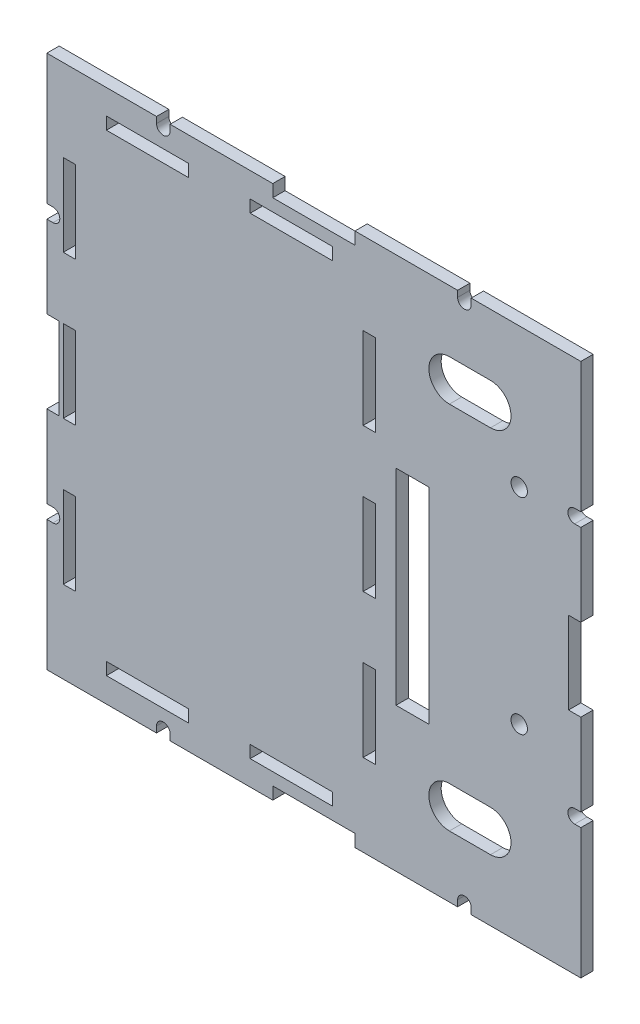
SolidWorks part; units mm, degrees
ref_plane "Front Plane" through (0, 0, 0) normal (0, 0, 1) x (1, 0, 0)
ref_plane "Top Plane" through (0, 0, 0) normal (0, 1, 0) x (1, 0, 0)
ref_plane "Right Plane" through (0, 0, 0) normal (1, 0, 0) x (0, 0, -1)
sketch "Sketch1" plane through (0, 0, 0) normal (0, 0, 1) x (1, 0, 0)
  line L0 (55, 0) -> (-55, 0) construction
  line L1 (65, -65) -> (-65, -65)
  line L2 (65, -65) -> (65, 65)
  line L3 (65, 65) -> (-65, 65)
  line L4 (-65, -65) -> (-65, 65)
  line L5 (65, -65) -> (-65, 65) construction
  line L6 (65, 65) -> (-65, -65) construction
  line L7 (10, 62) -> (-10, 62)
  line L8 (10, 62) -> (10, 65)
  line L9 (10, 65) -> (-10, 65)
  line L10 (-10, 62) -> (-10, 65)
  line L11 (10, 62) -> (-10, 65) construction
  line L12 (10, 65) -> (-10, 62) construction
  line L13 (-62, -10) -> (-65, -10)
  line L14 (-62, -10) -> (-62, 10)
  line L15 (-62, 10) -> (-65, 10)
  line L16 (-65, -10) -> (-65, 10)
  line L17 (-62, -10) -> (-65, 10) construction
  line L18 (-62, 10) -> (-65, -10) construction
  line L19 (10, -65) -> (-10, -65)
  line L20 (-10, -62) -> (-10, -65)
  line L21 (10, -62) -> (-10, -62)
  line L22 (10, -62) -> (10, -65)
  line L23 (0, -55) -> (0, 55) construction
  line L24 (62, 10) -> (65, 10)
  line L25 (65, -10) -> (65, 10)
  line L26 (62, -10) -> (65, -10)
  line L27 (62, -10) -> (62, 10)
  line L28 (-36.65, 63.5) -> (-36.65, 66.5) construction
  line L29 (-38.3, 63.5) -> (-38.3, 66.5)
  line L30 (-35, 63.5) -> (-35, 66.5)
  line L31 (-63.5, 31.65) -> (-66.5, 31.65) construction
  line L32 (-63.5, 30) -> (-66.5, 30)
  line L33 (-63.5, 33.3) -> (-66.5, 33.3)
  line L34 (36.65, 63.5) -> (36.65, 66.5) construction
  line L35 (38.3, 63.5) -> (38.3, 66.5)
  line L36 (35, 63.5) -> (35, 66.5)
  line L37 (63.5, 31.65) -> (66.5, 31.65) construction
  line L38 (63.5, 30) -> (66.5, 30)
  line L39 (63.5, 33.3) -> (66.5, 33.3)
  line L40 (63.5, -31.65) -> (66.5, -31.65) construction
  line L41 (63.5, -30) -> (66.5, -30)
  line L42 (63.5, -33.3) -> (66.5, -33.3)
  line L43 (36.65, -63.5) -> (36.65, -66.5) construction
  line L44 (38.3, -63.5) -> (38.3, -66.5)
  line L45 (35, -63.5) -> (35, -66.5)
  line L46 (-36.65, -63.5) -> (-36.65, -66.5) construction
  line L47 (-38.3, -63.5) -> (-38.3, -66.5)
  line L48 (-35, -63.5) -> (-35, -66.5)
  line L49 (-63.5, -31.65) -> (-66.5, -31.65) construction
  line L50 (-63.5, -30) -> (-66.5, -30)
  line L51 (-63.5, -33.3) -> (-66.5, -33.3)
  line L52 (-58, -45) -> (-61, -45)
  line L53 (-58, -10) -> (-61, -10)
  line L54 (-58, -10) -> (-58, 10)
  line L55 (-58, 10) -> (-61, 10)
  line L56 (-61, -10) -> (-61, 10)
  line L57 (-58, -10) -> (-61, 10) construction
  line L58 (-58, 10) -> (-61, -10) construction
  line L59 (-58, 25) -> (-61, 25)
  line L60 (-58, 25) -> (-58, 45)
  line L61 (-58, 45) -> (-61, 45)
  line L62 (-61, 25) -> (-61, 45)
  line L63 (-58, 25) -> (-61, 45) construction
  line L64 (-58, 45) -> (-61, 25) construction
  line L65 (-61, -25) -> (-61, -45)
  line L66 (-58, -25) -> (-61, -25)
  line L67 (-58, -25) -> (-58, -45)
  line L68 (-15.5, -59) -> (4.5, -59)
  line L69 (-30.5, 56) -> (-50.5, 56)
  line L70 (-30.5, 56) -> (-30.5, 59)
  line L71 (-30.5, 59) -> (-50.5, 59)
  line L72 (-50.5, 56) -> (-50.5, 59)
  line L73 (-30.5, 56) -> (-50.5, 59) construction
  line L74 (-30.5, 59) -> (-50.5, 56) construction
  line L75 (-15.5, 56) -> (4.5, 56)
  line L76 (-15.5, 56) -> (-15.5, 59)
  line L77 (-15.5, 59) -> (4.5, 59)
  line L78 (4.5, 56) -> (4.5, 59)
  line L79 (-15.5, 56) -> (4.5, 59) construction
  line L80 (-15.5, 59) -> (4.5, 56) construction
  line L81 (4.5, -56) -> (4.5, -59)
  line L82 (-15.5, -56) -> (4.5, -56)
  line L83 (-15.5, -56) -> (-15.5, -59)
  line L84 (-30.5, -59) -> (-50.5, -59)
  line L85 (-50.5, -56) -> (-50.5, -59)
  line L86 (-30.5, -56) -> (-50.5, -56)
  line L87 (-30.5, -56) -> (-30.5, -59)
  line L88 (43, -45) -> (33, -45) construction
  line L89 (12, 45) -> (15, 45)
  line L90 (12, 45) -> (12, 25)
  line L91 (12, 25) -> (15, 25)
  line L92 (15, 45) -> (15, 25)
  line L93 (12, 45) -> (15, 25) construction
  line L94 (12, 25) -> (15, 45) construction
  line L95 (15, -10) -> (12, -10)
  line L96 (15, -10) -> (15, 10)
  line L97 (15, 10) -> (12, 10)
  line L98 (12, -10) -> (12, 10)
  line L99 (15, -10) -> (12, 10) construction
  line L100 (15, 10) -> (12, -10) construction
  line L101 (12, -45) -> (15, -45)
  line L102 (12, -45) -> (12, -25)
  line L103 (12, -25) -> (15, -25)
  line L104 (15, -45) -> (15, -25)
  line L105 (12, -45) -> (15, -25) construction
  line L106 (12, -25) -> (15, -45) construction
  line L107 (28, -30) -> (20, -30)
  line L108 (28, -30) -> (28, 20)
  line L109 (28, 20) -> (20, 20)
  line L110 (20, -30) -> (20, 20)
  line L111 (28, -30) -> (20, 20) construction
  line L112 (28, 20) -> (20, -30) construction
  line L117 (43, 45) -> (33, 45) construction
  line L118 (43, 40) -> (33, 40)
  line L119 (43, 50) -> (33, 50)
  line L120 (43, -40) -> (33, -40)
  line L121 (43, -50) -> (33, -50)
  arc A0 (-38.3, 63.5) -> (-35, 63.5) centre (-36.65, 63.5) ccw
  arc A1 (-35, 66.5) -> (-38.3, 66.5) centre (-36.65, 66.5) ccw
  arc A2 (-63.5, 30) -> (-63.5, 33.3) centre (-63.5, 31.65) ccw
  arc A3 (-66.5, 33.3) -> (-66.5, 30) centre (-66.5, 31.65) ccw
  arc A4 (38.3, 63.5) -> (35, 63.5) centre (36.65, 63.5) cw
  arc A5 (35, 66.5) -> (38.3, 66.5) centre (36.65, 66.5) cw
  arc A6 (63.5, 30) -> (63.5, 33.3) centre (63.5, 31.65) cw
  arc A7 (66.5, 33.3) -> (66.5, 30) centre (66.5, 31.65) cw
  arc A8 (63.5, -30) -> (63.5, -33.3) centre (63.5, -31.65) ccw
  arc A9 (66.5, -33.3) -> (66.5, -30) centre (66.5, -31.65) ccw
  arc A10 (38.3, -63.5) -> (35, -63.5) centre (36.65, -63.5) ccw
  arc A11 (35, -66.5) -> (38.3, -66.5) centre (36.65, -66.5) ccw
  arc A12 (-38.3, -63.5) -> (-35, -63.5) centre (-36.65, -63.5) cw
  arc A13 (-35, -66.5) -> (-38.3, -66.5) centre (-36.65, -66.5) cw
  arc A14 (-63.5, -30) -> (-63.5, -33.3) centre (-63.5, -31.65) cw
  arc A15 (-66.5, -33.3) -> (-66.5, -30) centre (-66.5, -31.65) cw
  arc A20 (43, 40) -> (43, 50) centre (43, 45) ccw
  arc A21 (33, 50) -> (33, 40) centre (33, 45) ccw
  circle A22 centre (50, 31) radius 2
  circle A23 centre (50, -19) radius 2
  arc A24 (43, -40) -> (43, -50) centre (43, -45) cw
  arc A25 (33, -50) -> (33, -40) centre (33, -45) cw
  point P0 (0, 0)
  point P6 (0, 63.5)
  point P11 (-63.5, 0)
  point P16 (-36.65, 65)
  point P35 (-65, 31.65)
  point P42 (-59.5, 35)
  point P45 (36.65, 65)
  point P52 (65, 31.65)
  point P59 (65, -31.65)
  point P66 (36.65, -65)
  point P73 (-36.65, -65)
  point P80 (-65, -31.65)
  point P85 (-59.5, 0)
  point P94 (-5.5, 57.5)
  point P100 (-40.5, 57.5)
  point P108 (13.5, -35)
  point P117 (13.5, 35)
  point P123 (13.5, 0)
  point P132 (24, -5)
  point P138 (38, -45)
  point P143 (38, 45)
  dimension "D7" = 1.65
  dimension "D10" = 1.65
  dimension "D29" = 10
  dimension "D31" = 5
  dimension "D35" = 4
  dimension "D1" = 130
  dimension "D2" = 130
  dimension "D3" = 20
  dimension "D4" = 3
  dimension "D5" = 20
  dimension "D6" = 3
  dimension "D8" = 3
  dimension "D9" = 25
  dimension "D11" = 3
  dimension "D12" = 20
  dimension "D13" = 20
  dimension "D14" = 3
  dimension "D15" = 15
  dimension "D16" = 4
  dimension "D17" = 20
  dimension "D18" = 3
  dimension "D19" = 6
  dimension "D20" = 15
  dimension "D21" = 10.5
  dimension "D22" = 10.5
  dimension "D23" = 3
  dimension "D24" = 20
  dimension "D25" = 15
  dimension "D26" = 15
  dimension "D27" = 50
  dimension "D28" = 8
  dimension "5" = 35
  dimension "D30" = 37
  dimension "D32" = 15
  dimension "D33" = 27
  dimension "D36" = 31
  dimension "D37" = 50
  dimension "D38" = 50
extrude "Boss-Extrude1" add sketch "Sketch1" along normal blind 3 contours L26 L27 L24 L2 L3 L8 L7 L10 L4 L15 L14 L13 L1 L20 L21 L22
